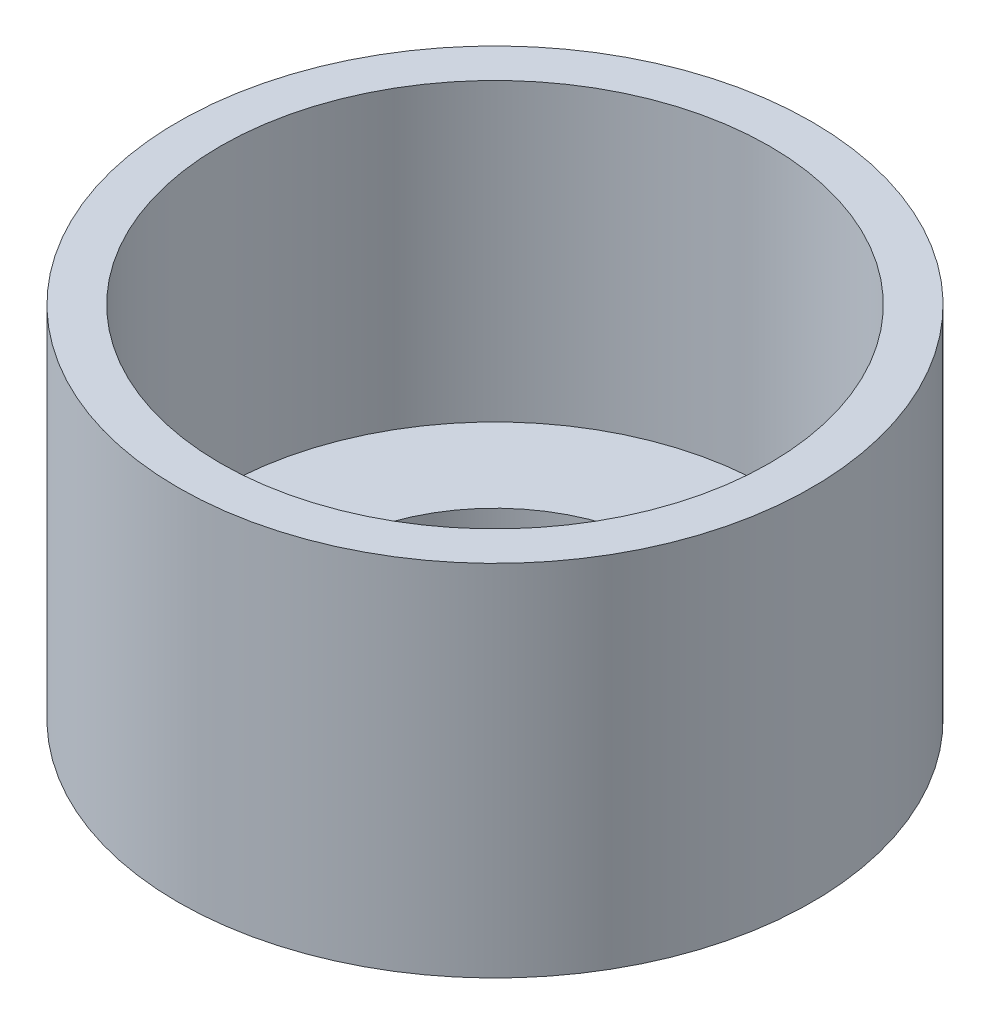
SolidWorks part; units mm, degrees
ref_plane "정면" through (0, 0, 0) normal (0, 0, 1) x (1, 0, 0)
ref_plane "윗면" through (0, 0, 0) normal (0, 1, 0) x (1, 0, 0)
ref_plane "우측면" through (0, 0, 0) normal (1, 0, 0) x (0, 0, -1)
sketch "스케치1" plane through (0, 0, 0) normal (0, 1, 0) x (1, 0, 0)
  circle A0 centre (0, 0) radius 8
  circle A1 centre (0, 0) radius 15
  dimension "D1" = 16
  dimension "D2" = 30
extrude "보스-돌출1" add sketch "스케치1" along normal blind 3
sketch "스케치2" plane through (0, 3, 0) normal (0, 1, 0) x (1, 0, 0)
  circle A0 centre (0, 0) radius 15
  circle A1 centre (0, 0) radius 13
  circle A2 centre (0, 0) radius 15 construction
  dimension "D1" = 26
extrude "보스-돌출2" add sketch "스케치2" along normal blind 14
